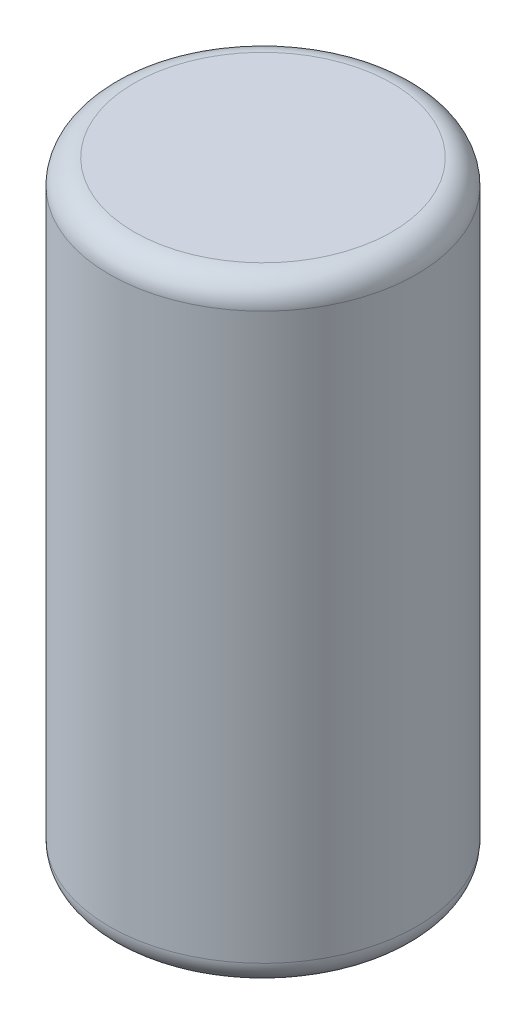
SolidWorks part; units mm, degrees
ref_plane "Front Plane" through (0, 0, 0) normal (0, 0, 1) x (1, 0, 0)
ref_plane "Top Plane" through (0, 0, 0) normal (0, 1, 0) x (1, 0, 0)
ref_plane "Right Plane" through (0, 0, 0) normal (1, 0, 0) x (0, 0, -1)
sketch "Sketch1" plane through (0, 0, 0) normal (0, 1, 0) x (1, 0, 0)
  circle A0 centre (0, 0) radius 62.5
  dimension "D1" = 125
extrude "Boss-Extrude1" add sketch "Sketch1" along normal blind 250
fillet "Fillet3" radius 10 2 edges at (0, 0, 62.5) (0, 250, 62.5)
